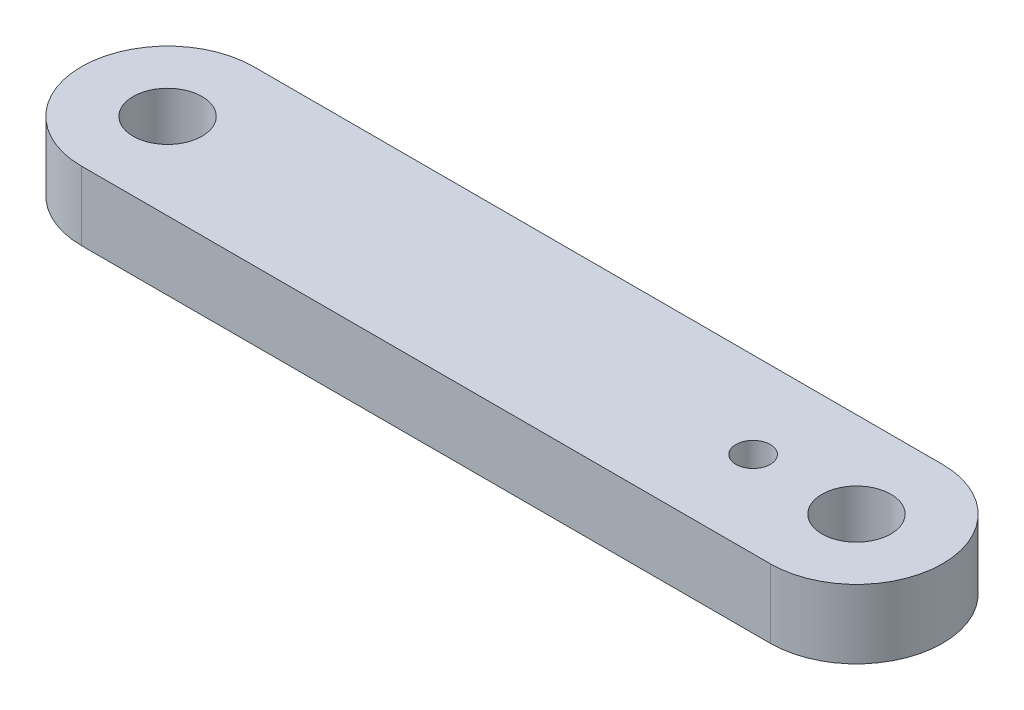
SolidWorks part; units mm, degrees
ref_plane "Front Plane" through (0, 0, 0) normal (0, 0, 1) x (1, 0, 0)
ref_plane "Top Plane" through (0, 0, 0) normal (0, 1, 0) x (1, 0, 0)
ref_plane "Right Plane" through (0, 0, 0) normal (1, 0, 0) x (0, 0, -1)
sketch "Sketch1" plane through (0, 0, 0) normal (0, 1, 0) x (1, 0, 0)
  line L0 (-10, 0) -> (10, 0) construction
  line L1 (-10, 2.5) -> (10, 2.5)
  line L2 (-10, -2.5) -> (10, -2.5)
  arc A0 (-10, 2.5) -> (-10, -2.5) centre (-10, 0) ccw
  arc A1 (10, -2.5) -> (10, 2.5) centre (10, 0) ccw
  circle A2 centre (10, 0) radius 1
  circle A3 centre (-10, 0) radius 1
  point P3 (0, 0)
  dimension "D3" = 2
  dimension "D4" = 2.5
  dimension "D5" = 2
  dimension "D1" = 20
  dimension "D12" = 10
extrude "Boss-Extrude1" add sketch "Sketch1" along normal blind 2
sketch "Sketch2" plane through (0, 2, 0) normal (0, 1, 0) x (1, 0, 0)
  circle A0 centre (7, 0) radius 0.5
  circle A1 centre (10, 0) radius 1 construction
  dimension "D1" = 1
  dimension "D2" = 3
  dimension "D3" = 7
extrude "Cut-Extrude1" cut sketch "Sketch2" against normal blind 10
